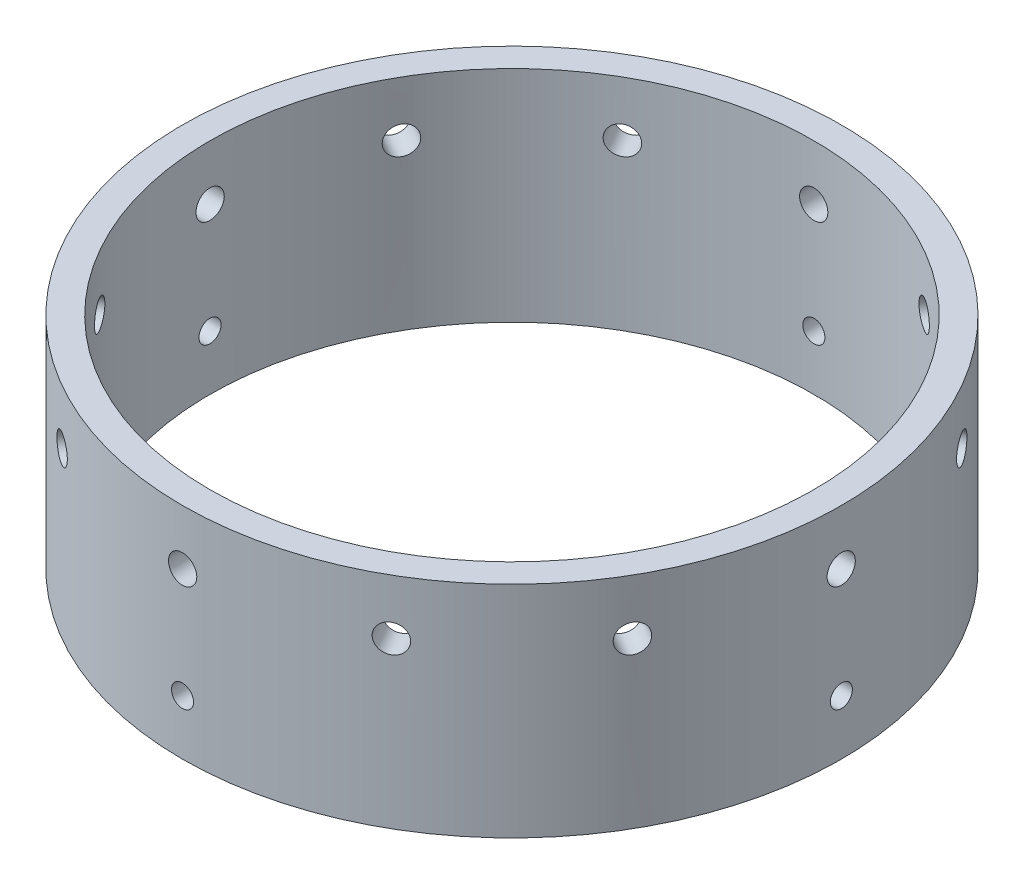
SolidWorks part; units mm, degrees
ref_plane "Front Plane" through (0, 0, 0) normal (0, 0, 1) x (1, 0, 0)
ref_plane "Top Plane" through (0, 0, 0) normal (0, 1, 0) x (1, 0, 0)
ref_plane "Right Plane" through (0, 0, 0) normal (1, 0, 0) x (0, 0, -1)
sketch "Sketch2" plane through (0, 0, 0) normal (0, 1, 0) x (1, 0, 0)
  circle A0 centre (0, 0) radius 76.2
  circle A1 centre (0, 0) radius 69.85
  dimension "D1" = 139.7
  dimension "D2" = 152.4
extrude "Boss-Extrude1" add sketch "Sketch2" along normal blind 50.8
sketch "Sketch3" plane through (0, 0, 0) normal (0, 0, 1) x (1, 0, 0)
  line L0 (-76.2, 0) -> (76.2, 0) construction
  line L1 (76.2, 50.8) -> (-76.2, 50.8) construction
  line L2 (76.2, 50.8) -> (-76.2, 50.8) construction
  line L3 (-76.2, 0) -> (76.2, 0) construction
  line L4 (0, 25.4) -> (0, 50.8) construction
  line L7 (-76.2, 25.4) -> (76.2, 25.4) construction
  line L8 (-76.2, 50.8) -> (-76.2, 0) construction
  line L9 (76.2, 0) -> (76.2, 50.8) construction
  line L11 (0, 0) -> (0, 25.4) construction
  circle A0 centre (0, 12.7) radius 3.2639
  circle A1 centre (0, 38.1) radius 3.2639
  dimension "D2" = 6.5278
  dimension "D1" = 6.5278
  dimension "D3" = 12.7
  dimension "D4" = 12.7
extrude "Cut-Extrude1" cut sketch "Sketch3" against normal through all contours A1
pattern_circular "CirPattern1" count 12 over 360 about axis through (0, 50.8, 0) along (0, 1, 0) of "Cut-Extrude1"
ref_plane "Plane1" through (0, 0, 76.2) normal (0, 0, 1) x (1, 0, 0)
sketch "Sketch7" plane through (0, 0, 76.2) normal (0, 0, 1) x (1, 0, 0)
  circle A1 centre (0, 38.1) radius 3.2639
  circle A2 centre (0, 38.1) radius 3.2639 construction
  circle A3 centre (0, 12.7) radius 3.2639
  circle A4 centre (0, 12.7) radius 3.2639 construction
  point P0 (0, 12.7)
  dimension "D1" = 0
  dimension "D2" = 0
hole_wizard "1/4-20 Tapped Hole2" positions "Sketch7" profile "Sketch8" tap size "1/4-20" standard "ANSI Inch"
sketch "Sketch8" plane through (0, 12.7, 76.2) normal (1, 0, 0) x (0, -1, 0)
  line L0 (0, 0) -> (0, 6.35)
  line L1 (0, 6.35) -> (2.5527, 6.35)
  line L2 (2.5527, 6.35) -> (2.5527, 0)
  line L5 (2.5527, 0) -> (0, 0)
  line L11 (0, -6.35) -> (0, 107.95) construction
  dimension "Thru Tap Drill Dia." = 5.1054
  dimension "Thru Tap Drill Depth" = 6.35
cosmetic thread "Hole Thread2" parameters "D2"=6.35
pattern_circular "CirPattern3" count 4 over 360 about axis through (0, 50.8, 0) along (0, 1, 0) of "1/4-20 Tapped Hole2"
cosmetic thread "Hole Thread3" parameters "D2"=6.35
cosmetic thread "Hole Thread4" parameters "D2"=6.35
cosmetic thread "Hole Thread5" parameters "D2"=6.35
